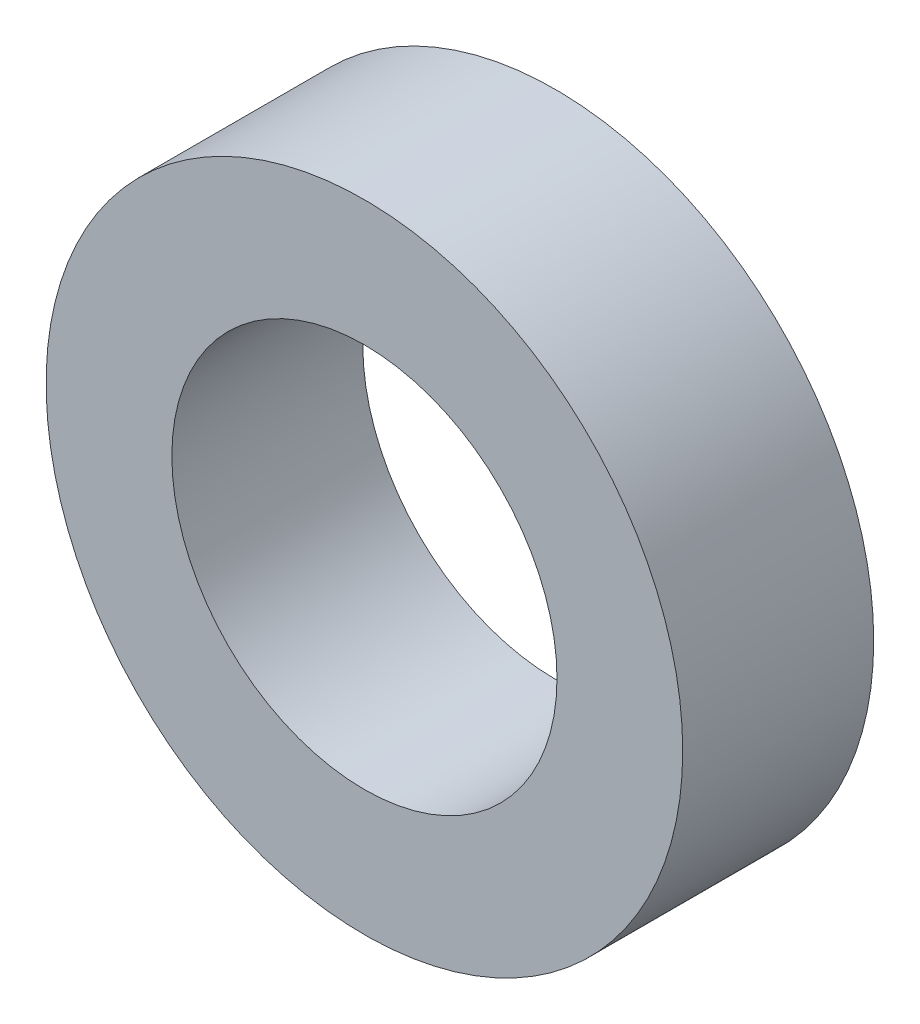
SolidWorks part; units mm, degrees
material "Custom Plastic"
ref_plane "X-Y Datum" through (0, 0, 0) normal (0, 0, 1) x (1, 0, 0)
ref_plane "X-Z Datum" through (0, 0, 0) normal (0, 1, 0) x (1, 0, 0)
ref_plane "Y-Z Datum" through (0, 0, 0) normal (1, 0, 0) x (0, 0, -1)
sketch "Sketch1" plane through (0, 0, 0) normal (0, 0, 1) x (1, 0, 0)
  circle A0 centre (0, 0) radius 3.025
  circle A1 centre (0, 0) radius 5
  dimension "D1" = 6.05
  dimension "D2" = 10
extrude "Boss-Extrude1" add sketch "Sketch1" along normal blind 3
